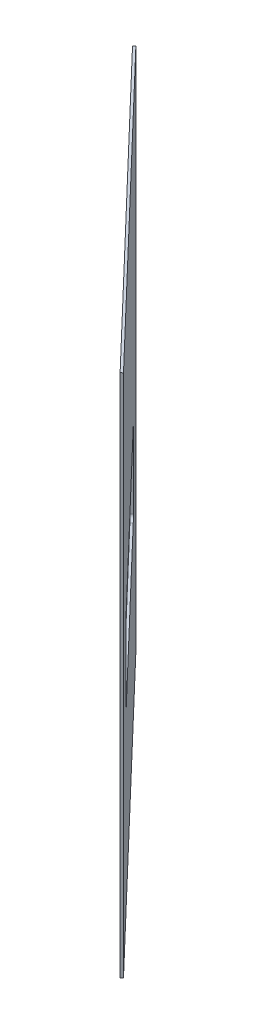
SolidWorks part; units mm, degrees
ref_plane "Front Plane" through (0, 0, 0) normal (0, 0, 1) x (1, 0, 0)
ref_plane "Top Plane" through (0, 0, 0) normal (0, 1, 0) x (1, 0, 0)
ref_plane "Right Plane" through (0, 0, 0) normal (1, 0, 0) x (0, 0, -1)
sketch "Sketch1" plane through (6993.28, 0, -6693.4576) normal (-0.7224, 0, 0.6915) x (0.6915, 0, 0.7224)
  line L4 (-2080.8481, 1403.35) -> (-2080.8481, 6.35)
  line L5 (-2080.8481, 6.35) -> (-1014.0481, 6.35)
  line L6 (-1014.0481, 6.35) -> (-1014.0481, 1403.35)
  line L7 (-1014.0481, 1403.35) -> (-2080.8481, 1403.35)
  line L8 (-2080.8481, 1403.35) -> (-2080.8481, 6.35)
  line L9 (-2080.8481, 6.35) -> (-1014.0481, 6.35)
  line L10 (-1014.0481, 6.35) -> (-1014.0481, 1403.35)
  line L11 (-1014.0481, 1403.35) -> (-2080.8481, 1403.35)
  line L16 (-1242.6481, 685.8) -> (-1852.2481, 685.8)
  line L17 (-1229.9481, 476.25) -> (-1229.9481, 673.1)
  line L18 (-1852.2481, 463.55) -> (-1242.6481, 463.55)
  line L19 (-1864.9481, 673.1) -> (-1864.9481, 476.25)
  line L20 (-1242.6481, 685.8) -> (-1852.2481, 685.8)
  line L21 (-1229.9481, 476.25) -> (-1229.9481, 673.1)
  line L22 (-1852.2481, 463.55) -> (-1242.6481, 463.55)
  line L23 (-1864.9481, 673.1) -> (-1864.9481, 476.25)
  arc A4 (-1852.2481, 685.8) -> (-1864.9481, 673.1) centre (-1852.2481, 673.1) ccw
  arc A5 (-1229.9481, 673.1) -> (-1242.6481, 685.8) centre (-1242.6481, 673.1) ccw
  arc A6 (-1242.6481, 463.55) -> (-1229.9481, 476.25) centre (-1242.6481, 476.25) ccw
  arc A7 (-1864.9481, 476.25) -> (-1852.2481, 463.55) centre (-1852.2481, 476.25) ccw
  arc A8 (-1852.2481, 685.8) -> (-1864.9481, 673.1) centre (-1852.2481, 673.1) ccw
  arc A9 (-1229.9481, 673.1) -> (-1242.6481, 685.8) centre (-1242.6481, 673.1) ccw
  arc A10 (-1242.6481, 463.55) -> (-1229.9481, 476.25) centre (-1242.6481, 476.25) ccw
  arc A11 (-1864.9481, 476.25) -> (-1852.2481, 463.55) centre (-1852.2481, 476.25) ccw
  dimension "D1" = 0
  dimension "D2" = 0
extrude "Boss-Extrude1" add sketch "Sketch1" against normal up to surface (6.35 mm away)
